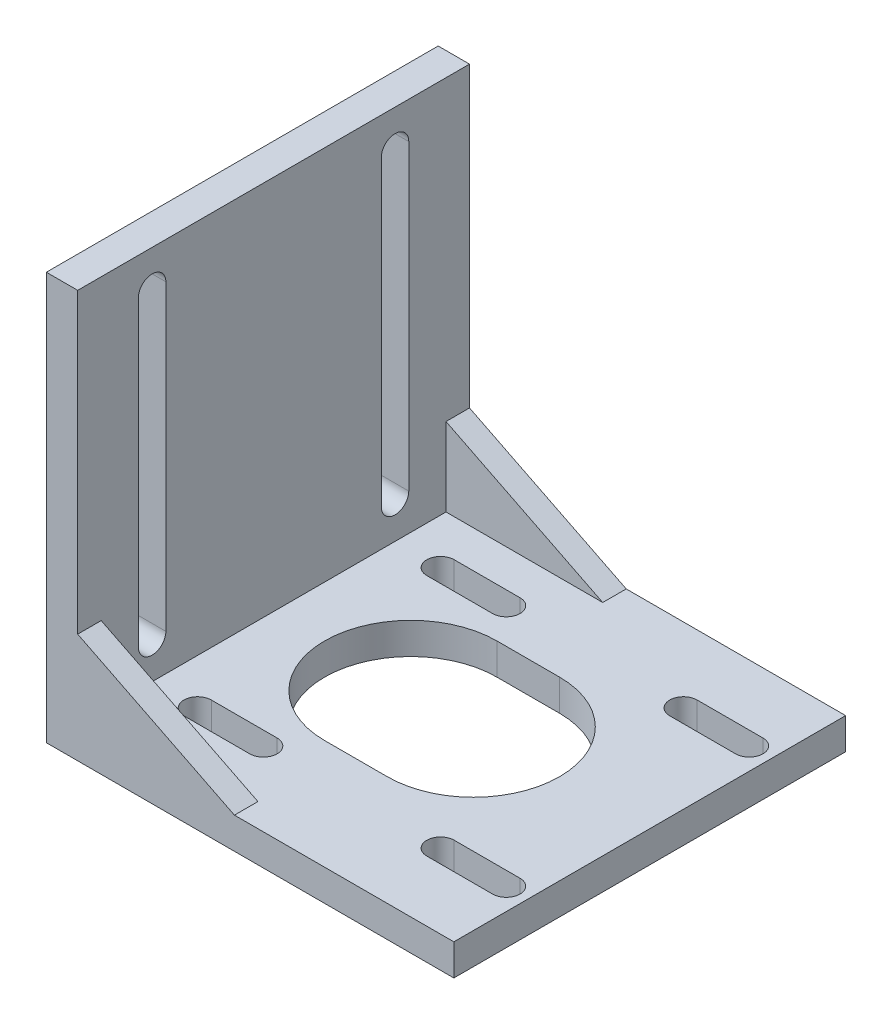
SolidWorks part; units mm, degrees
ref_plane "Front Plane" through (0, 0, 0) normal (0, 0, 1) x (1, 0, 0)
ref_plane "Top Plane" through (0, 0, 0) normal (0, 1, 0) x (1, 0, 0)
ref_plane "Right Plane" through (0, 0, 0) normal (1, 0, 0) x (0, 0, -1)
sketch "Sketch1" plane through (0, 0, 0) normal (0, 1, 0) x (1, 0, 0)
  line L1 (-26, 25) -> (26, 25)
  line L2 (-26, 25) -> (-26, -25)
  line L3 (-26, -25) -> (26, -25)
  line L4 (26, 25) -> (26, -25)
  line L5 (-26, 25) -> (26, -25) construction
  line L6 (-26, -25) -> (26, 25) construction
  circle A0 centre (0, 0) radius 5.5418 construction
  point P0 (0, 0)
  dimension "D1" = 50
  dimension "D2" = 52
extrude "Boss-Extrude1" add sketch "Sketch1" along normal blind 4
sketch "Sketch2" plane through (0, 4, 0) normal (0, 1, 0) x (1, 0, 0)
  line L0 (26, 25) -> (-26, 25) construction
  line L1 (-19, 25) -> (26, -25) construction
  line L3 (-12, 15.5) -> (19, 15.5)
  line L4 (-12, 15.5) -> (-12, -15.5)
  line L5 (-12, -15.5) -> (19, -15.5)
  line L6 (19, 15.5) -> (19, -15.5)
  line L7 (-12, 15.5) -> (19, -15.5) construction
  line L8 (-12, -15.5) -> (19, 15.5) construction
  circle A0 centre (19, 15.5) radius 1.75
  circle A1 centre (-12, -15.5) radius 1.75
  circle A2 centre (19, -15.5) radius 1.75
  circle A3 centre (-12, 15.5) radius 1.75
  circle A4 centre (3.5, 0) radius 11
  point P0 (-19, 25)
  point P7 (3.5, 0)
  dimension "D4" = 3.5
  dimension "D5" = 3.5
  dimension "D6" = 22
  dimension "D1" = 45
  dimension "D3" = 31
extrude "Cut-Extrude1" cut sketch "Sketch2" against normal through all contours A3 | A1 | A4 | A0 | A2
sketch "Sketch3" plane through (0, 4, 0) normal (0, 1, 0) x (1, 0, 0)
  line L0 (26, 25) -> (-26, 25) construction
  line L1 (-26, -25) -> (26, -25) construction
  line L2 (-26, 25) -> (-22, 25)
  line L3 (-26, 25) -> (-26, -25)
  line L4 (-26, -25) -> (-22, -25)
  line L5 (-22, 25) -> (-22, -25)
  point P0 (-22, 25)
  dimension "D1" = 4
  dimension "D2" = 4
extrude "Boss-Extrude3" add sketch "Sketch3" along normal blind 48
sketch "Sketch5" plane through (0, 0, 25) normal (0, 0, 1) x (1, 0, 0)
  line L1 (-22, 4) -> (-2, 4)
  line L2 (-22, 4) -> (-22, 14)
  line L3 (-22, 14) -> (-2, 14)
  line L4 (-2, 4) -> (-2, 14)
  dimension "D1" = 10
  dimension "D2" = 20
extrude "Boss-Extrude4" add sketch "Sketch5" against normal up to surface (50 mm away)
sketch "Sketch7" plane through (0, 14, 0) normal (0, 1, 0) x (1, 0, 0)
  line L0 (-22, 25) -> (-2, -25) construction
  line L2 (-22, 22) -> (-2, 22)
  line L3 (-22, 22) -> (-22, -22)
  line L4 (-22, -22) -> (-2, -22)
  line L5 (-2, 22) -> (-2, -22)
  line L6 (-22, 22) -> (-2, -22) construction
  line L7 (-22, -22) -> (-2, 22) construction
  point P4 (-12, 0)
  dimension "D1" = 44
  dimension "D2" = 20
extrude "Cut-Extrude2" cut sketch "Sketch7" against normal up to surface (10 mm away) up to face at (10.0833, 4, 0)
sketch "Sketch8" plane through (0, 0, 25) normal (0, 0, 1) x (1, 0, 0)
  line L0 (-22, 14) -> (-2, 4)
  line L1 (-2, 4) -> (-2, 14)
  line L2 (-2, 14) -> (-22, 14)
extrude "Cut-Extrude3" cut sketch "Sketch8" against normal through all
sketch "Sketch9" plane through (-26, 0, 0) normal (-1, 0, 0) x (0, 0, 1)
  line L0 (25, 52) -> (25, 0) construction
  line L1 (-25, 52) -> (25, 4) construction
  line L2 (-15.5, 47.3151) -> (-15.5, 8.6849) construction
  line L3 (-15.5, 43.5) -> (15.5, 43.5)
  line L4 (-15.5, 43.5) -> (-15.5, 12.5)
  line L5 (-15.5, 12.5) -> (15.5, 12.5)
  line L6 (15.5, 43.5) -> (15.5, 12.5)
  line L7 (-15.5, 43.5) -> (15.5, 12.5) construction
  line L8 (-15.5, 12.5) -> (15.5, 43.5) construction
  line L9 (-13.75, 47.3151) -> (-13.75, 8.6849)
  line L10 (-17.25, 47.3151) -> (-17.25, 8.6849)
  line L11 (15.5, 47.3151) -> (15.5, 8.6849) construction
  line L12 (17.25, 47.3151) -> (17.25, 8.6849)
  line L13 (13.75, 47.3151) -> (13.75, 8.6849)
  arc A0 (-13.75, 47.3151) -> (-17.25, 47.3151) centre (-15.5, 47.3151) ccw
  arc A1 (-17.25, 8.6849) -> (-13.75, 8.6849) centre (-15.5, 8.6849) ccw
  arc A2 (17.25, 47.3151) -> (13.75, 47.3151) centre (15.5, 47.3151) ccw
  arc A3 (13.75, 8.6849) -> (17.25, 8.6849) centre (15.5, 8.6849) ccw
  point P0 (25, 4)
  point P7 (0, 28)
  point P14 (-15.5, 28)
  point P20 (15.5, 28)
  dimension "D1" = 4
  dimension "D2" = 31
  dimension "D3" = 31
  dimension "D4" = 1.75
  dimension "D5" = 1.75
extrude "Cut-Extrude5" cut sketch "Sketch9" against normal through all contours L10 A1 L9 A0 | L13 A3 L12 A2
sketch "Sketch11" plane through (0, 4, 0) normal (0, 1, 0) x (1, 0, 0)
  line L0 (-16.2, 15.5) -> (-7.8, 15.5) construction
  line L1 (-16.2, 17.25) -> (-7.8, 17.25)
  line L2 (-16.2, 13.75) -> (-7.8, 13.75)
  line L3 (-12, 15.5) -> (-11.4468, 17.1603) construction
  line L4 (3.5, 0) -> (-4.2893, 0) construction
  line L5 (-4.2893, 0) -> (3.5, 0) construction
  line L6 (3.5, 0) -> (3.5, 5.3279) construction
  line L7 (-16.2, -15.5) -> (-7.8, -15.5) construction
  line L8 (-16.2, -17.25) -> (-7.8, -17.25)
  line L9 (-16.2, -13.75) -> (-7.8, -13.75)
  line L10 (23.2, 15.5) -> (14.8, 15.5) construction
  line L11 (23.2, 13.75) -> (14.8, 13.75)
  line L12 (23.2, 17.25) -> (14.8, 17.25)
  line L13 (23.2, -15.5) -> (14.8, -15.5) construction
  line L14 (23.2, -13.75) -> (14.8, -13.75)
  line L15 (23.2, -17.25) -> (14.8, -17.25)
  arc A0 (-16.2, 17.25) -> (-16.2, 13.75) centre (-16.2, 15.5) ccw
  arc A1 (-7.8, 13.75) -> (-7.8, 17.25) centre (-7.8, 15.5) ccw
  circle A2 centre (-12, 15.5) radius 1.75 construction
  arc A3 (-16.2, -17.25) -> (-16.2, -13.75) centre (-16.2, -15.5) cw
  arc A4 (-7.8, -13.75) -> (-7.8, -17.25) centre (-7.8, -15.5) cw
  arc A5 (23.2, 13.75) -> (23.2, 17.25) centre (23.2, 15.5) ccw
  arc A6 (14.8, 17.25) -> (14.8, 13.75) centre (14.8, 15.5) ccw
  arc A7 (23.2, -13.75) -> (23.2, -17.25) centre (23.2, -15.5) cw
  arc A8 (14.8, -17.25) -> (14.8, -13.75) centre (14.8, -15.5) cw
  point P2 (-12, 15.5)
  point P19 (-12, -15.5)
  point P26 (19, 15.5)
  point P34 (19, -15.5)
  dimension "D3" = 1.75
  dimension "D4" = 1.75
  dimension "D1" = 8.4
  dimension "D2" = 1.75
  dimension "D5" = 8.4
  dimension "D6" = 8.4
  dimension "D7" = 8.4
extrude "Cut-Extrude6" cut sketch "Sketch11" against normal through all
sketch "Sketch12" plane through (0, 0, 0) normal (0, -1, 0) x (1, 0, 0)
  line L0 (3.5, 0) -> (-4.5, 0) construction
  line L1 (3.5, -11) -> (-4.5, -11)
  line L2 (3.5, 11) -> (-4.5, 11)
  arc A1 (3.5, -11) -> (3.5, 11) centre (3.5, 0) ccw
  arc A2 (-4.5, 11) -> (-4.5, -11) centre (-4.5, 0) ccw
  point P2 (-0.5, 0)
  dimension "D2" = 11
  dimension "D1" = 8
extrude "Cut-Extrude7" cut sketch "Sketch12" against normal through all
sketch "Sketch16" plane through (0, 4, 0) normal (0, 1, 0) x (1, 0, 0)
  line L0 (-12, -13.75) -> (-12, -17.25) construction
  line L1 (-7.8, -13.75) -> (-16.2, -13.75) construction
  line L2 (-16.2, -17.25) -> (-7.8, -17.25) construction
  line L3 (-6.05, -15.5) -> (-17.95, -15.5) construction
  line L4 (19, 17.25) -> (19, 13.75) construction
  line L5 (23.2, 17.25) -> (14.8, 17.25) construction
  line L6 (14.8, 13.75) -> (23.2, 13.75) construction
  line L7 (24.95, 15.5) -> (13.05, 15.5) construction
  arc A0 (-7.8, -17.25) -> (-7.8, -13.75) centre (-7.8, -15.5) ccw construction
  arc A1 (-16.2, -13.75) -> (-16.2, -17.25) centre (-16.2, -15.5) ccw construction
  arc A2 (23.2, 13.75) -> (23.2, 17.25) centre (23.2, 15.5) ccw construction
  arc A3 (14.8, 17.25) -> (14.8, 13.75) centre (14.8, 15.5) ccw construction
sketch "Sketch19" plane through (0, 0, 0) normal (0, -1, 0) x (1, 0, 0)
  circle A0 centre (0, 0) radius 5.2991 construction
